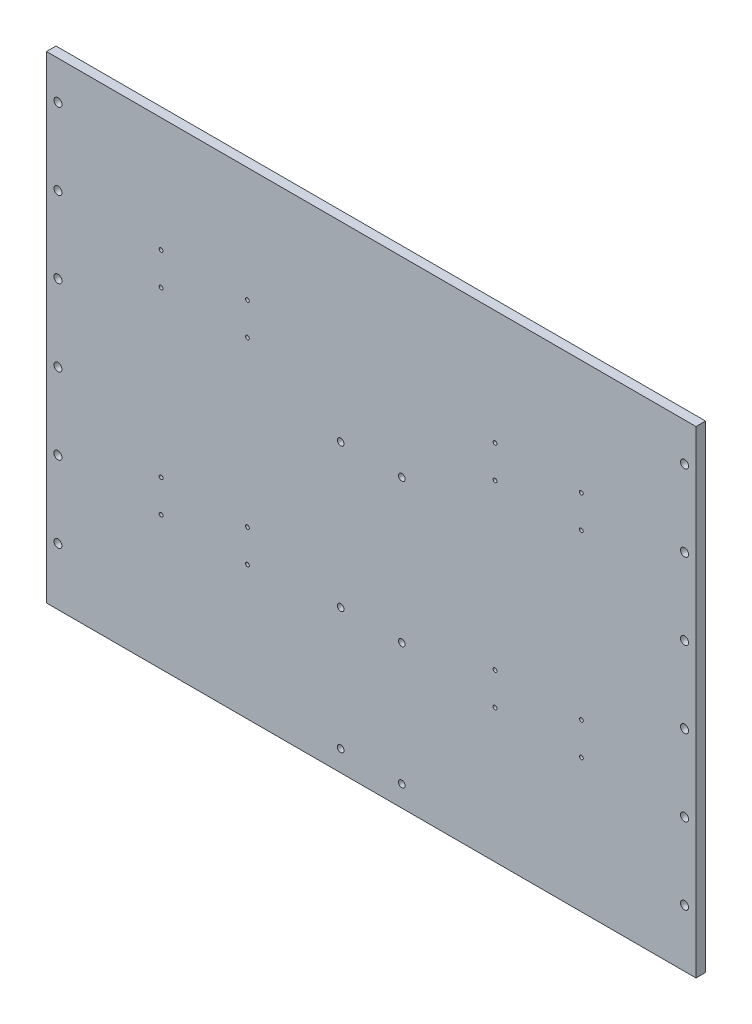
SolidWorks part; units mm, degrees
ref_plane "前视基准面" through (0, 0, 0) normal (0, 0, 1) x (1, 0, 0)
ref_plane "上视基准面" through (0, 0, 0) normal (0, 1, 0) x (1, 0, 0)
ref_plane "右视基准面" through (0, 0, 0) normal (1, 0, 0) x (0, 0, -1)
other "Configuration Table"
sketch "草图1" plane through (0, 0, 0) normal (0, 0, 1) x (1, 0, 0)
  line L0 (0, 0) -> (106.7347, 0) construction
  line L6 (-170, -120) -> (-170, 120)
  line L7 (-170, 120) -> (170, 120)
  line L8 (170, -120) -> (170, 120)
  line L9 (-170, -120) -> (170, 120) construction
  line L10 (-170, 120) -> (170, -120) construction
  line L11 (0, 0) -> (0, 44.5419) construction
  line L12 (-64.8, -60) -> (-64.8, -43) construction
  line L13 (-110, 60) -> (-64.8, 60) construction
  line L14 (-110, 60) -> (-110, 43) construction
  line L15 (-110, 43) -> (-64.8, 43) construction
  line L16 (-64.8, 60) -> (-64.8, 43) construction
  line L17 (-110, -43) -> (-64.8, -43) construction
  line L18 (-110, -60) -> (-110, -43) construction
  line L19 (-110, -60) -> (-64.8, -60) construction
  line L20 (110, -60) -> (64.8, -60) construction
  line L21 (110, -60) -> (110, -43) construction
  line L22 (110, -43) -> (64.8, -43) construction
  line L23 (64.8, 60) -> (64.8, 43) construction
  line L24 (110, 43) -> (64.8, 43) construction
  line L25 (110, 60) -> (110, 43) construction
  line L26 (110, 60) -> (64.8, 60) construction
  line L27 (64.8, -60) -> (64.8, -43) construction
  line L28 (-170, -120) -> (170, -120) construction
  line L29 (-16, -119) -> (16, -119) construction
  line L30 (-16, -119) -> (-16, -55) construction
  line L31 (-16, -55) -> (16, -55) construction
  line L32 (16, -119) -> (16, -55) construction
  line L33 (-16, -119) -> (16, -55) construction
  line L34 (-16, -55) -> (16, -119) construction
  line L36 (-170, -120) -> (-170, -130)
  line L37 (-170, -130) -> (170, -130)
  line L38 (170, -120) -> (170, -130)
  line L39 (-16, 20) -> (16, 20) construction
  circle A0 centre (-110, 60) radius 1
  circle A1 centre (-64.8, 60) radius 1
  circle A2 centre (-64.8, 43) radius 1
  circle A3 centre (-110, 43) radius 1
  circle A4 centre (-110, -43) radius 1
  circle A5 centre (-64.8, -43) radius 1
  circle A6 centre (-64.8, -60) radius 1
  circle A7 centre (-110, -60) radius 1
  circle A8 centre (110, -60) radius 1
  circle A9 centre (64.8, -60) radius 1
  circle A10 centre (64.8, -43) radius 1
  circle A11 centre (110, -43) radius 1
  circle A12 centre (110, 43) radius 1
  circle A13 centre (64.8, 43) radius 1
  circle A14 centre (64.8, 60) radius 1
  circle A15 centre (110, 60) radius 1
  circle A16 centre (-16, 20) radius 1.75
  circle A17 centre (16, 20) radius 1.75
  circle A18 centre (16, -55) radius 1.75
  circle A19 centre (16, -119) radius 1.75
  circle A20 centre (-16, -55) radius 1.75
  circle A21 centre (-16, -119) radius 1.75
  point P0 (0, 0)
  point P46 (-14.9546, 20)
  dimension "D3" = 45.2
  dimension "D5" = 2
  dimension "D6" = 2
  dimension "D7" = 2
  dimension "D8" = 2
  dimension "D12" = 3.5
  dimension "D13" = 64
  dimension "D16" = 3.5
  dimension "D11" = 3.5
  dimension "D20" = 16
  dimension "D1" = 240
  dimension "D2" = 340
  dimension "D4" = 17
  dimension "D9" = 60
  dimension "D10" = 60
  dimension "D14" = 32
  dimension "D15" = 55
  dimension "D17" = 16
  dimension "D18" = 10
  dimension "D19" = 20
  dimension "D21" = 32
extrude "凸台-拉伸1" add sketch "草图1" along normal blind 5
sketch "草图2" plane through (0, 0, 5) normal (0, 0, 1) x (1, 0, 0)
  line L1 (-170, -120) -> (-170, 120) construction
  line L3 (-170, 120) -> (170, 120) construction
  line L4 (-164, 100) -> (-164, 60) construction
  line L5 (-164, 60) -> (-164, 20) construction
  circle A0 centre (-164, 100) radius 2.1
  circle A1 centre (-164, 60) radius 2.1
  circle A3 centre (-164, 20) radius 2.1
  dimension "D2" = 4.2
  dimension "D1" = 6
  dimension "D3" = 20
  dimension "D4" = 40
extrude "切除-拉伸1" cut sketch "草图2" against normal blind 10
mirror "镜向1" about plane through (0, 0, 0) normal (0, 1, 0) of "切除-拉伸1"
mirror "镜向2" about plane through (0, 0, 0) normal (1, 0, 0) of "镜向1", "切除-拉伸1"
